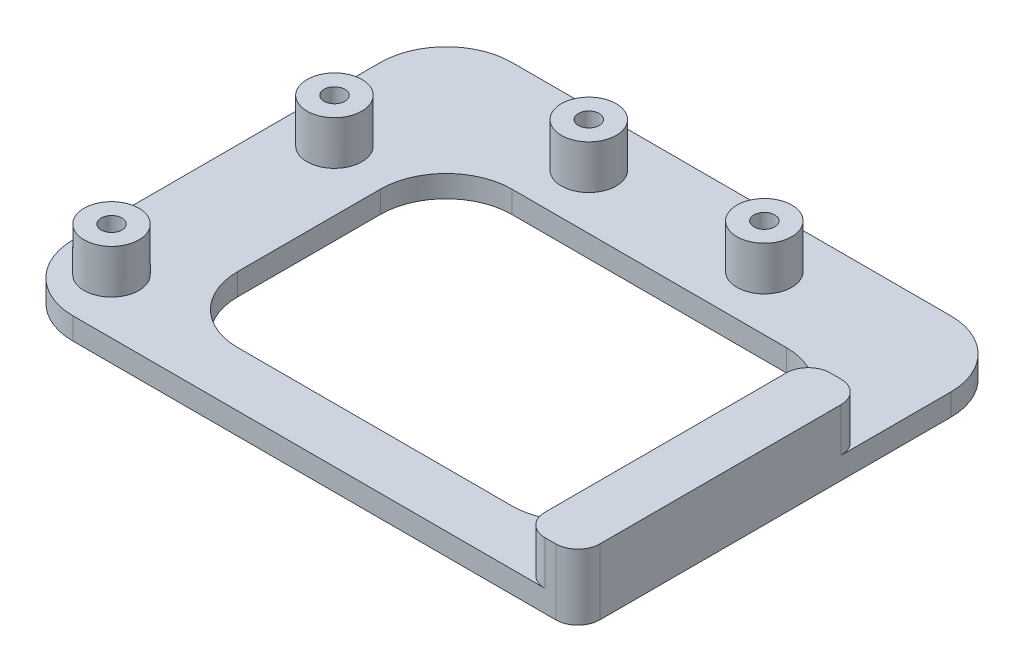
SolidWorks part; units mm, degrees
ref_plane "Front Plane" through (0, 0, 0) normal (0, 0, 1) x (1, 0, 0)
ref_plane "Top Plane" through (0, 0, 0) normal (0, 1, 0) x (1, 0, 0)
ref_plane "Right Plane" through (0, 0, 0) normal (1, 0, 0) x (0, 0, -1)
sketch "Sketch1" plane through (0, 0, 0) normal (0, 1, 0) x (1, 0, 0)
  line L1 (-26, -20) -> (26, -20)
  line L2 (-26, -20) -> (-26, 20)
  line L3 (-26, 20) -> (26, 20)
  line L4 (26, -20) -> (26, 20)
  line L5 (-26, -20) -> (26, 20) construction
  line L6 (-26, 20) -> (26, -20) construction
  point P0 (0, 0)
  dimension "D1" = 52
  dimension "D2" = 40
extrude "Boss-Extrude1" add sketch "Sketch1" along normal blind 2
sketch "Sketch2" plane through (0, 2, 0) normal (0, 1, 0) x (1, 0, 0)
  line L0 (0, 0) -> (0, -50000) construction
  line L1 (-26, -20) -> (26, -20) construction
  line L2 (-21.5, -15) -> (21.5, -15) construction
  line L3 (-21.5, -15) -> (-21.5, 5.32) construction
  line L4 (-21.5, 5.32) -> (21.5, 5.32) construction
  line L5 (21.5, -15) -> (21.5, 5.32) construction
  line L6 (-21.5, -15) -> (21.5, 5.32) construction
  line L7 (-21.5, 5.32) -> (21.5, -15) construction
  line L8 (-8, 15) -> (8, 15) construction
  line L9 (26, 20) -> (-26, 20) construction
  circle A0 centre (8, 15) radius 0.95
  circle A1 centre (-8, 15) radius 0.95
  circle A2 centre (-21.5, 5.32) radius 0.95
  circle A3 centre (-21.5, -15) radius 0.95
  point P3 (0, -4.84)
  point P13 (0, 15)
  point P17 (21.5, -4.84)
  point P24 (19, -15)
  point P25 (19, -17.5362)
  dimension "D6" = 1.9
  dimension "D7" = 1.9
  dimension "D1" = 43
  dimension "D2" = 20.32
  dimension "D3" = 5
  dimension "D4" = 16
  dimension "D5" = 5
extrude "Cut-Extrude1" cut sketch "Sketch2" against normal through all
sketch "Sketch3" plane through (0, 2, 0) normal (0, 1, 0) x (1, 0, 0)
  circle A0 centre (-21.5, 5.32) radius 2.5
  circle A1 centre (-21.5, -15) radius 2.5
  circle A4 centre (8, 15) radius 2.5
  circle A5 centre (-8, 15) radius 2.5
  circle A6 centre (-8, 15) radius 0.95 construction
  circle A7 centre (8, 15) radius 0.95 construction
  circle A10 centre (-21.5, -15) radius 0.95 construction
  circle A11 centre (-21.5, 5.32) radius 0.95 construction
  circle A12 centre (-21.5, 5.32) radius 0.95
  circle A13 centre (-21.5, -15) radius 0.95
  circle A16 centre (8, 15) radius 0.95
  circle A17 centre (-8, 15) radius 0.95
  dimension "D1" = 5
  dimension "D2" = 5
extrude "Boss-Extrude2" add sketch "Sketch3" along normal blind 4
sketch "Sketch4" plane through (0, 2, 0) normal (0, 1, 0) x (1, 0, 0)
  line L1 (26, -20) -> (21, -20)
  line L2 (26, -20) -> (26, 6)
  line L3 (26, 6) -> (21, 6)
  line L4 (21, -20) -> (21, 6)
  dimension "D1" = 26
  dimension "D2" = 5
extrude "Boss-Extrude3" add sketch "Sketch4" along normal up to surface (4 mm away) up to face at (-21.5, 6, -2.82)
sketch "Sketch5" plane through (0, 2, 0) normal (0, 1, 0) x (1, 0, 0)
  line L0 (-26, 20) -> (-26, -20) construction
  line L1 (21, 10) -> (-16, 10)
  line L2 (21, 10) -> (21, -15)
  line L3 (21, -15) -> (-16, -15)
  line L4 (-16, 10) -> (-16, -15)
  line L5 (21, 10) -> (-16, -15) construction
  line L6 (21, -15) -> (-16, 10) construction
  line L7 (-26, -20) -> (21, -20) construction
  line L8 (26, 20) -> (-26, 20) construction
  line L9 (26, 6) -> (26, 20) construction
  point P0 (2.5, -2.5)
  dimension "D1" = 10
  dimension "D2" = 5
  dimension "D3" = 10
  dimension "D4" = 5
extrude "Cut-Extrude2" cut sketch "Sketch5" against normal through all
fillet "Fillet1" radius 2 4 edges at (26, 3, 20) (21, 4, 20) (26, 4, -6) (21, 4, -6)
fillet "Fillet2" radius 6 7 edges at (21, 1, 15) (-26, 1, 20) (-16, 1, 15) (-16, 1, -10) (-26, 1, -20) (26, 1, -20) (21, 1, -10)
